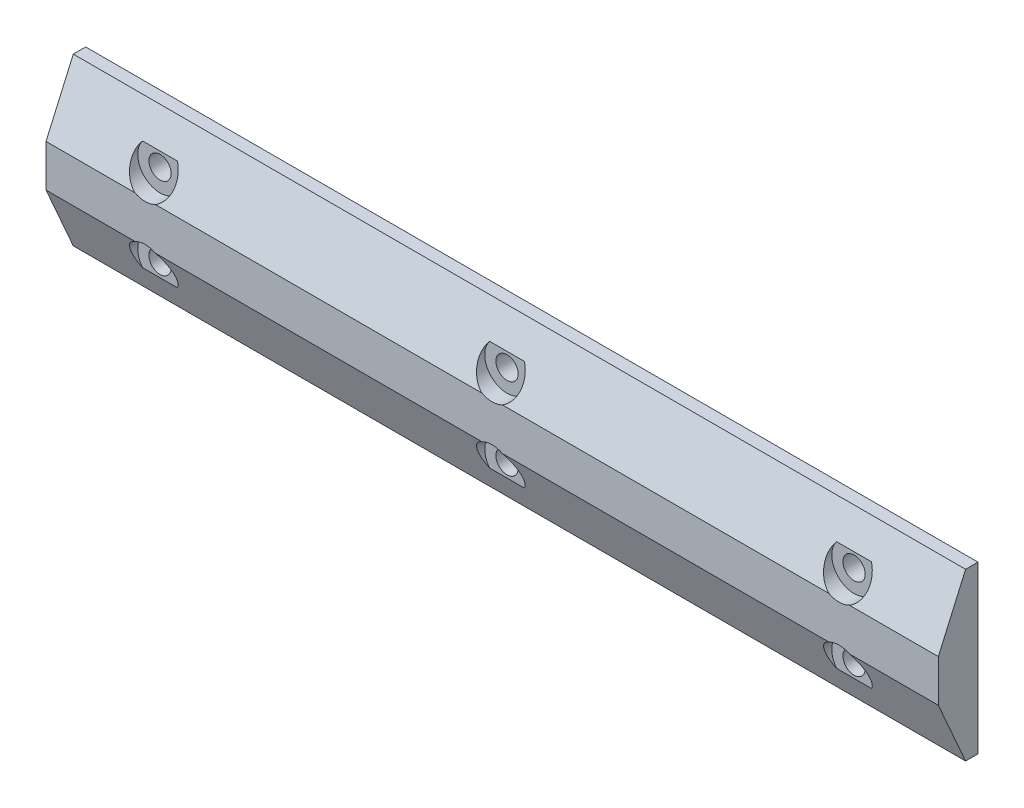
SolidWorks part; units mm, degrees
material "PVC 0.007 Plasticizado"
ref_plane "Plano frontal" through (0, 0, 0) normal (0, 0, 1) x (1, 0, 0)
ref_plane "Plano superior" through (0, 0, 0) normal (0, 1, 0) x (1, 0, 0)
ref_plane "Plano direito" through (0, 0, 0) normal (1, 0, 0) x (0, 0, -1)
sketch "Esboço1" plane through (0, 0, 0) normal (0, 0, 1) x (1, 0, 0)
  line L1 (0, 0) -> (360, 0)
  line L2 (0, 0) -> (0, 67)
  line L3 (0, 67) -> (360, 67)
  line L4 (360, 0) -> (360, 67)
  dimension "D1" = 360
  dimension "D2" = 67
extrude "Ressalto-extrusão1" add sketch "Esboço1" along normal blind 16
sketch "Esboço2" plane through (0, 0, 0) normal (-1, 0, 0) x (0, 0, 1)
  line L0 (5, 0) -> (16, 25)
  line L1 (16, 0) -> (0, 0) construction
  line L2 (16, 67) -> (16, 0) construction
  line L3 (5, 67) -> (16, 42)
  line L5 (5, 67) -> (16, 67)
  line L6 (16, 67) -> (16, 42)
  line L7 (16, 25) -> (16, 0)
  line L8 (16, 0) -> (5, 0)
  line L9 (16, 67) -> (0, 67) construction
  line L10 (0, 67) -> (0, 0) construction
  dimension "D1" = 5
  dimension "D2" = 5
  dimension "D3" = 25
  dimension "D4" = 25
extrude "Corte-extrusão1" cut sketch "Esboço2" against normal through all
hole_wizard "Rebaixo para parafuso com cabeça panela de M81" positions "Esboço3" profile "Esboço4" counterbore size "M8" standard "ISO" end condition through all
sketch "Esboço3" plane through (0, 0, 16) normal (0, 0, 1) x (1, 0, 0)
  line L0 (40, 50) -> (320, 50) construction
  line L2 (40, 17) -> (320, 17) construction
  line L4 (360, 67) -> (0, 67) construction
  line L5 (360, 0) -> (0, 0) construction
  line L6 (0, 67) -> (0, 42) construction
  line L7 (0, 25) -> (0, 0) construction
  line L8 (360, 67) -> (360, 42) construction
  line L9 (360, 25) -> (360, 0) construction
  point P0 (40, 50)
  point P2 (40, 17)
  point P4 (180, 50)
  point P6 (180, 17)
  point P8 (320, 50)
  point P10 (320, 17)
  dimension "D1" = 17
  dimension "D2" = 17
  dimension "D3" = 40
  dimension "D4" = 40
  dimension "D5" = 40
  dimension "D6" = 40
sketch "Esboço4" plane through (40, 50, 16) normal (1, 0, 0) x (0, -1, 0)
  line L0 (0, 0) -> (0, 16)
  line L1 (0, 16) -> (4.5, 16)
  line L3 (4.5, 16) -> (4.5, 6)
  line L4 (4.5, 6) -> (9, 6)
  line L5 (9, 6) -> (9, 0)
  line L7 (9, 0) -> (0, 0)
  line L11 (0, -6.35) -> (0, 107.95) construction
  dimension "Thru Hole Dia." = 9
  dimension "Thru Hole Depth" = 16
  dimension "C'Bore Dia." = 18
  dimension "C'Bore Depth" = 6
